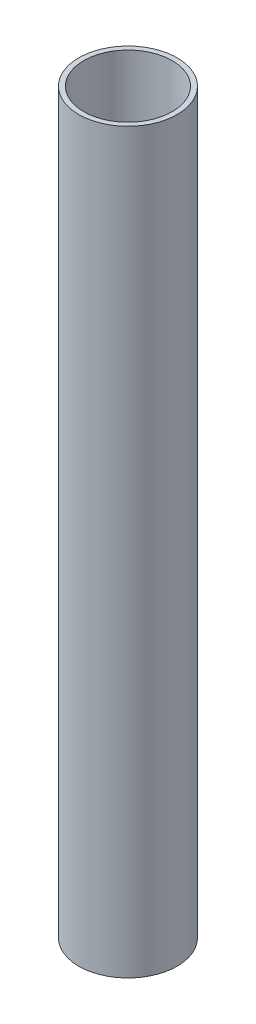
SolidWorks part; units mm, degrees
material "High-Strength Lightweight"
ref_plane "Front Plane" through (0, 0, 0) normal (0, 0, 1) x (1, 0, 0)
ref_plane "Top Plane" through (0, 0, 0) normal (0, 1, 0) x (1, 0, 0)
ref_plane "Right Plane" through (0, 0, 0) normal (1, 0, 0) x (0, 0, -1)
sketch "Sketch1" plane through (0, 0, 0) normal (0, 1, 0) x (1, 0, 0)
  circle A0 centre (0, 0) radius 10
  circle A1 centre (0, 0) radius 9
  dimension "D1" = 20
  dimension "D2" = 18
extrude "Boss-Extrude1" add sketch "Sketch1" along normal blind 150
